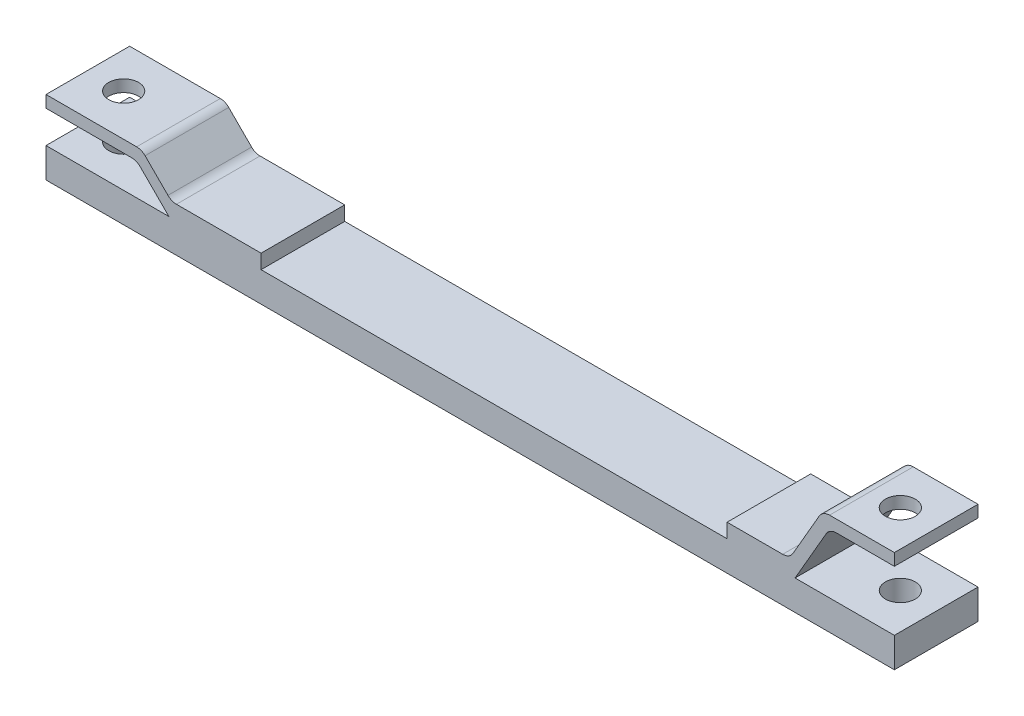
SolidWorks part; units mm, degrees
ref_plane "Front Plane" through (0, 0, 0) normal (0, 0, 1) x (1, 0, 0)
ref_plane "Top Plane" through (0, 0, 0) normal (0, 1, 0) x (1, 0, 0)
ref_plane "Right Plane" through (0, 0, 0) normal (1, 0, 0) x (0, 0, -1)
sketch "Sketch1" plane through (0, 0, 0) normal (0, 0, 1) x (1, 0, 0)
  line L0 (-355, 12.5) -> (-355, 49.5) construction
  line L1 (-355, 12.5) -> (355, 12.5)
  line L2 (-355, 12.5) -> (-355, -12.5)
  line L3 (-355, -12.5) -> (355, -12.5)
  line L4 (355, 12.5) -> (355, -12.5)
  line L5 (-355, 12.5) -> (355, -12.5) construction
  line L6 (-355, -12.5) -> (355, 12.5) construction
  line L7 (-355, 49.5) -> (-275, 49.5)
  line L8 (-275, 49.5) -> (-250, 24.5)
  line L9 (-250, 24.5) -> (-175, 24.5)
  line L10 (-175, 24.5) -> (-175, 12.5)
  line L11 (355, 12.5) -> (355, 72.5) construction
  line L12 (355, 72.5) -> (295, 72.5)
  line L13 (295, 72.5) -> (267.2872, 24.5)
  line L14 (267.2872, 24.5) -> (215, 24.5)
  line L15 (215, 24.5) -> (215, 12.5)
  line L16 (-355, 39.5) -> (-279.1421, 39.5)
  line L17 (-279.1421, 39.5) -> (-254.1421, 14.5)
  line L18 (355, 72.5) -> (355, 62.5)
  line L19 (-355, 39.5) -> (-355, 49.5)
  line L20 (355, 62.5) -> (300.7735, 62.5)
  line L21 (300.7735, 62.5) -> (273.0607, 14.5)
  line L24 (273.0607, 14.5) -> (271.906, 12.5)
  line L25 (-254.1421, 14.5) -> (-252.1421, 12.5)
  line L26 (-254.1421, 14.5) -> (-185, 14.5) construction
  line L27 (-185, 14.5) -> (-185, 12.5) construction
  line L28 (273.0607, 14.5) -> (225, 14.5) construction
  line L29 (225, 14.5) -> (225, 12.5) construction
  point P0 (0, 0)
  dimension "D1" = 710
  dimension "D2" = 25
  dimension "D3" = 12
  dimension "D4" = 80
  dimension "D5" = 37
  dimension "D6" = 45
  dimension "D7" = 180
  dimension "D8" = 60
  dimension "D9" = 60
  dimension "D10" = 60
  dimension "D11" = 12
  dimension "D12" = 140
  dimension "D13" = 10
  dimension "D14" = 10
extrude "Boss-Extrude1" add sketch "Sketch1" along normal blind 70 contours L17 L25 L1 L10 L9 L8 L7 L19 L16 | L4 L1 L2 L3 | L24 L21 L20 L18 L12 L13 L14 L15 L1
fillet "Fillet1" radius 10 6 edges at (267.2872, 24.5, 35) (295, 72.5, 35) (300.7735, 62.5, 35) (-279.1421, 39.5, 35) (-250, 24.5, 35) (-275, 49.5, 35)
sketch "Sketch2" plane through (0, 72.5, 0) normal (0, 1, 0) x (1, 0, 0)
  line L0 (-355, -70) -> (-355, 0) construction
  line L1 (-355, 0) -> (-279.1421, 0) construction
  line L2 (355, -70) -> (355, 0) construction
  line L3 (355, -70) -> (300.7735, -70) construction
  circle A0 centre (325, -35) radius 12.5
  circle A1 centre (-325, -35) radius 12.5
  dimension "D1" = 25
  dimension "D2" = 25
  dimension "D3" = 30
  dimension "D4" = 35
  dimension "D5" = 30
  dimension "D6" = 35
extrude "Cut-Extrude1" cut sketch "Sketch2" against normal blind 100
